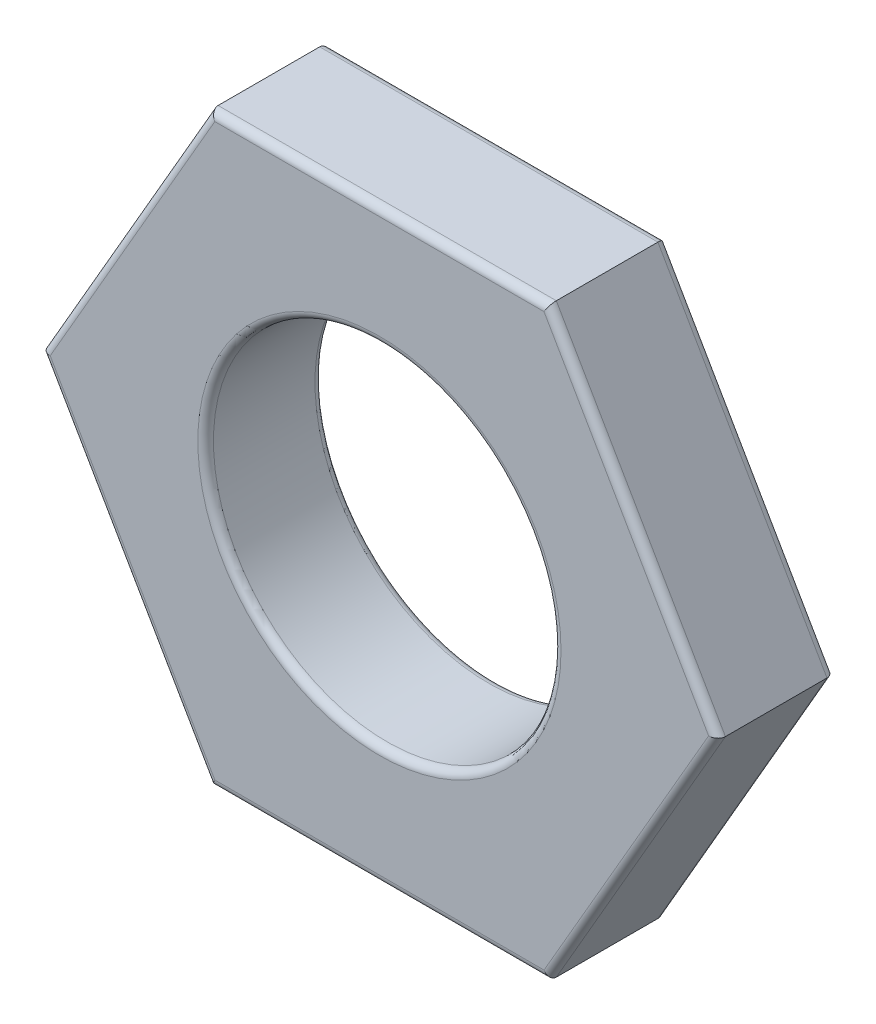
SolidWorks part; units mm, degrees
ref_plane "前视基准面" through (0, 0, 0) normal (0, 0, 1) x (1, 0, 0)
ref_plane "上视基准面" through (0, 0, 0) normal (0, 1, 0) x (1, 0, 0)
ref_plane "右视基准面" through (0, 0, 0) normal (1, 0, 0) x (0, 0, -1)
sketch "草图1" plane through (0, 0, 0) normal (0, 0, 1) x (1, 0, 0)
  line L0 (8.25, 0) -> (-8.25, 0) construction
  line L1 (21.6506, -37.5) -> (43.3013, 0)
  line L2 (43.3013, 0) -> (21.6506, 37.5)
  line L3 (21.6506, 37.5) -> (-21.6506, 37.5)
  line L4 (-21.6506, 37.5) -> (-43.3013, 0)
  line L5 (-43.3013, 0) -> (-21.6506, -37.5)
  line L6 (-21.6506, -37.5) -> (21.6506, -37.5)
  circle A0 centre (0, 0) radius 37.5 construction
  dimension "D1" = 75
extrude "拉伸1" add sketch "草图1" along normal blind 15
sketch "草图2" plane through (0, 0, 15) normal (0, 0, 1) x (1, 0, 0)
  circle A0 centre (0, 0) radius 22.25
  dimension "D1" = 44.5
extrude "拉伸2" cut sketch "草图2" against normal through all
fillet "圆角1" radius 1 14 edges at (22.25, 0, 0) (22.25, 0, 15) (-32.476, -18.75, 15) (0, -37.5, 15) (32.476, -18.75, 15) (32.476, 18.75, 15) (0, 37.5, 15) (-32.476, 18.75, 15) (0, 37.5, 0) (32.476, 18.75, 0) (32.476, -18.75, 0) (0, -37.5, 0) (-32.476, -18.75, 0) (-32.476, 18.75, 0)
